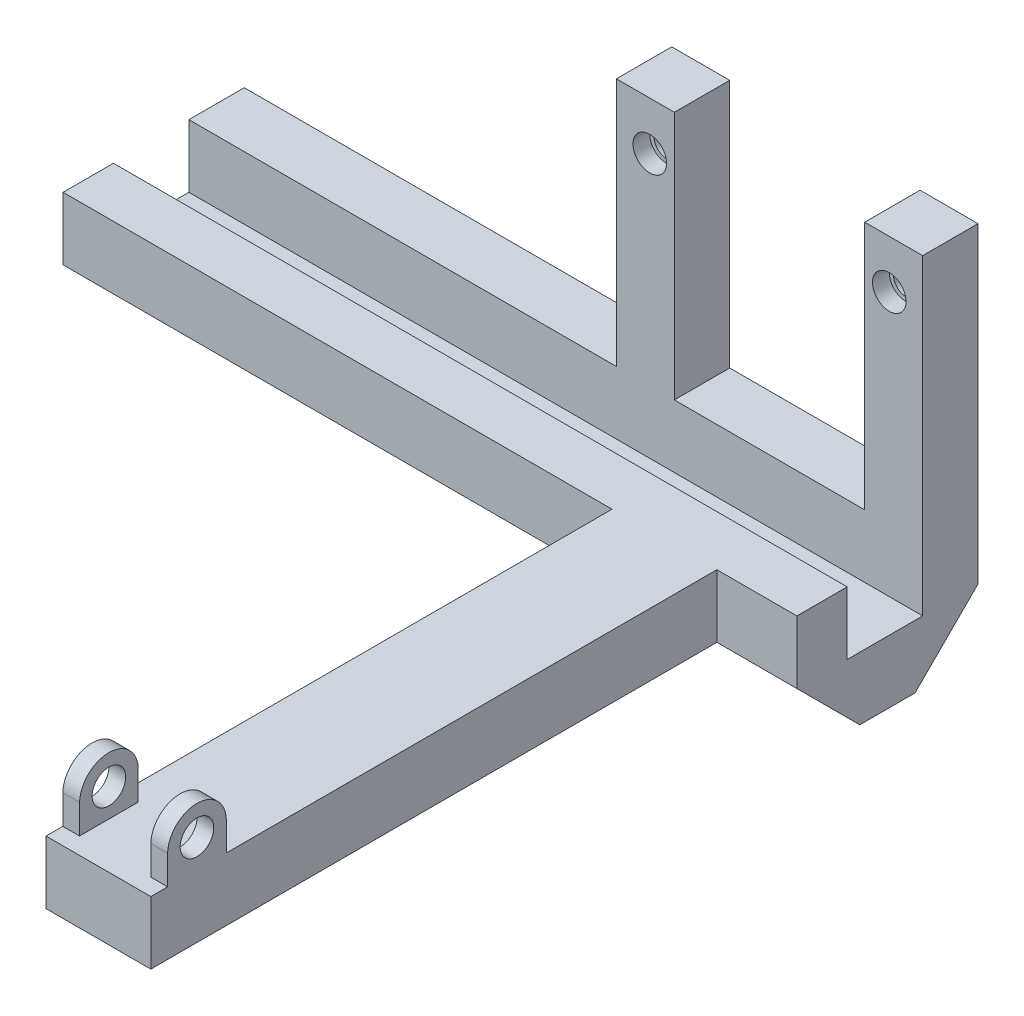
SolidWorks part; units mm, degrees
ref_plane "Front Plane" through (0, 0, 0) normal (0, 0, 1) x (1, 0, 0)
ref_plane "Top Plane" through (0, 0, 0) normal (0, 1, 0) x (1, 0, 0)
ref_plane "Right Plane" through (0, 0, 0) normal (1, 0, 0) x (0, 0, -1)
sketch "Sketch1" plane through (0, 0, 0) normal (0, 0, 1) x (1, 0, 0)
  line L0 (0, 0) -> (0, -26.56)
  line L17 (0, -26.56) -> (-71.9839, -26.56)
  line L18 (-71.9839, -26.56) -> (-71.9839, -11.56)
  line L19 (-71.9839, -11.56) -> (-52.61, -11.56)
  line L20 (-52.61, -11.56) -> (-52.61, 0)
  line L21 (-52.61, 0) -> (-37.61, 0)
  line L22 (-37.61, 0) -> (-37.61, -11.56)
  line L23 (-37.61, -11.56) -> (-15, -11.56)
  line L24 (-15, -11.56) -> (-15, 0)
  line L25 (-15, 0) -> (0, 0)
  dimension "D1" = 15
  dimension "D2" = 22.61
  dimension "D3" = 15
  dimension "D4" = 71.9839
  dimension "D5" = 15
  dimension "D6" = 0
  dimension "D7" = 11.56
extrude "Boss-Extrude1" add sketch "Sketch1" along normal blind 15
sketch "Sketch2" plane through (0, 0, 15) normal (0, 0, 1) x (1, 0, 0)
  line L0 (0, -26.56) -> (0, 0) construction
  line L1 (-71.9839, -26.56) -> (0, -26.56)
  line L2 (-71.9839, -26.56) -> (-71.9839, -19.06)
  line L3 (-71.9839, -19.06) -> (0, -19.06)
  line L4 (0, -26.56) -> (0, -19.06)
  dimension "D1" = 7.5
extrude "Boss-Extrude2" add sketch "Sketch2" along normal blind 15
sketch "Sketch3" plane through (0, -19.06, 0) normal (0, 1, 0) x (1, 0, 0)
  line L0 (0, -30) -> (0, -15) construction
  line L1 (-71.9839, -30) -> (0, -30)
  line L2 (-71.9839, -30) -> (-71.9839, -22.5)
  line L3 (-71.9839, -22.5) -> (0, -22.5)
  line L4 (0, -30) -> (0, -22.5)
extrude "Boss-Extrude3" add sketch "Sketch3" along normal blind 7.5
sketch "Sketch4" plane through (0, 0, 0) normal (1, 0, 0) x (0, 0, -1)
  line L0 (-30, -26.56) -> (0, -26.56) construction
  line L1 (-8.4, -26.56) -> (0, -26.56)
  line L2 (-8.4, -26.56) -> (-8.4, 0)
  line L3 (-8.4, 0) -> (0, 0)
  line L4 (0, -26.56) -> (0, 0)
  line L5 (-15, -19.06) -> (-15, 0) construction
  dimension "D1" = 6.6
extrude "Cut-Extrude1" cut sketch "Sketch4" against normal through all
sketch "Sketch5" plane through (0, 0, 8.4) normal (0, 0, -1) x (-1, 0, 0)
  line L0 (71.9839, -11.56) -> (71.9839, -26.56) construction
  line L1 (0, -26.56) -> (71.9839, -26.56)
  line L2 (0, -26.56) -> (0, -16.56)
  line L3 (0, -16.56) -> (71.9839, -16.56)
  line L4 (71.9839, -26.56) -> (71.9839, -16.56)
  dimension "D1" = 10
extrude "Boss-Extrude4" add sketch "Sketch5" along normal blind 23.8
sketch "Sketch6" plane through (-71.9839, 0, 0) normal (-1, 0, 0) x (0, 0, 1)
  line L1 (34.6627, -37.2189) -> (-26.9292, -37.2189)
  line L2 (34.6627, -37.2189) -> (34.6627, 2.9063)
  line L3 (34.6627, 2.9063) -> (-26.9292, 2.9063)
  line L4 (-26.9292, -37.2189) -> (-26.9292, 2.9063)
extrude "Cut-Extrude2" cut sketch "Sketch6" against normal blind 1.984
sketch "Esquisse1" plane through (0, 0, 15) normal (0, 0, 1) x (1, 0, 0)
  line L0 (-15, 0) -> (-15, -11.56) construction
  line L1 (-15, 0) -> (-4.91, 0)
  line L2 (-15, 0) -> (-15, -11.56)
  line L3 (-15, -11.56) -> (-4.91, -11.56)
  line L4 (-4.91, 0) -> (-4.91, -11.56)
  line L5 (0, 0) -> (-15, 0) construction
  line L6 (-15, -11.56) -> (-37.61, -11.56) construction
  line L7 (0, -19.06) -> (0, 0) construction
  dimension "D1" = 0
  dimension "D2" = 0
  dimension "D3" = 4.91
extrude "Enlèv. mat.-Extru.1" cut sketch "Esquisse1" against normal blind 10
sketch "Esquisse2" plane through (0, 0, 8.4) normal (0, 0, -1) x (-1, 0, 0)
  line L0 (4.91, -11.56) -> (37.61, -11.56) construction
  line L1 (27.61, -11.56) -> (32.52, -11.56)
  line L2 (27.61, -11.56) -> (27.61, 0)
  line L3 (27.61, 0) -> (32.52, 0)
  line L4 (32.52, -11.56) -> (32.52, 0)
  line L5 (4.91, -11.56) -> (4.91, 0) construction
  dimension "D1" = 22.7
  dimension "D2" = 4.91
  dimension "D3" = 11.56
extrude "Boss.-Extru.1" add sketch "Esquisse2" against normal blind 6.6
sketch "Esquisse3" plane through (0, 0, 30) normal (0, 0, 1) x (1, 0, 0)
  line L0 (-69.9999, -11.56) -> (0, -11.56) construction
  line L1 (-7.54, -11.56) -> (-20.04, -11.56)
  line L2 (-7.54, -11.56) -> (-7.54, -26.56)
  line L3 (-7.54, -26.56) -> (-20.04, -26.56)
  line L4 (-20.04, -11.56) -> (-20.04, -26.56)
  line L5 (-69.9999, -26.56) -> (0, -26.56) construction
  line L6 (0, -26.56) -> (0, -11.56) construction
  dimension "D1" = 12.5
  dimension "D2" = 7.54
extrude "Boss.-Extru.5" add sketch "Esquisse3" along normal blind 67.5
sketch "Esquisse4" plane through (0, -16.56, 0) normal (0, 1, 0) x (1, 0, 0)
  line L1 (-27.61, -8.4) -> (-4.91, -8.4)
  line L2 (-27.61, -8.4) -> (-27.61, 8.8)
  line L3 (-27.61, 8.8) -> (-4.91, 8.8)
  line L4 (-4.91, -8.4) -> (-4.91, 8.8)
  dimension "D1" = 17.2
  dimension "D2" = 22.7
extrude "Boss.-Extru.6" add sketch "Esquisse4" along normal blind 5
sketch "Esquisse5" plane through (0, 0, 8.4) normal (0, 0, -1) x (-1, 0, 0)
  line L1 (37.61, 0) -> (52.61, 0)
  line L2 (37.61, 0) -> (37.61, -11.56)
  line L3 (37.61, -11.56) -> (52.61, -11.56)
  line L4 (52.61, 0) -> (52.61, -11.56)
extrude "Enlèv. mat.-Extru.4" cut sketch "Esquisse5" against normal through all
sketch "Sketch7" plane through (0, 0, 0) normal (1, 0, 0) x (0, 0, -1)
  line L1 (-22.5, -11.56) -> (-24, -11.56)
  line L2 (-22.5, -11.56) -> (-22.5, -19.06)
  line L3 (-22.5, -19.06) -> (-24, -19.06)
  line L4 (-24, -11.56) -> (-24, -19.06)
  dimension "D1" = 1.5
  dimension "D2" = 7.5
extrude "Cut-Extrude3" cut sketch "Sketch7" against normal through all
sketch "Sketch8" plane through (0, 0, 97.5) normal (0, 0, 1) x (1, 0, 0)
  line L0 (-69.9999, -26.56) -> (-20.04, -26.56) construction
  line L1 (-20.04, -11.56) -> (-22.04, -11.56)
  line L2 (-20.04, -11.56) -> (-20.04, -26.56)
  line L3 (-20.04, -26.56) -> (-22.04, -26.56)
  line L4 (-22.04, -11.56) -> (-22.04, -26.56)
  dimension "D1" = 2
extrude "Boss-Extrude5" add sketch "Sketch8" against normal up to next
sketch "Sketch9" plane through (0, 0, 97.5) normal (0, 0, 1) x (1, 0, 0)
  line L0 (-22.04, -26.56) -> (-7.54, -26.56) construction
  line L1 (-7.54, -11.56) -> (-9.54, -11.56)
  line L2 (-7.54, -11.56) -> (-7.54, -26.56)
  line L3 (-7.54, -26.56) -> (-9.54, -26.56)
  line L4 (-9.54, -11.56) -> (-9.54, -26.56)
  dimension "D1" = 2
extrude "Cut-Extrude4" cut sketch "Sketch9" against normal blind 67.5
sketch "Sketch10" plane through (0, 0, 15) normal (0, 0, 1) x (1, 0, 0)
  line L0 (-9.54, -11.56) -> (0, -11.56) construction
  line L1 (-4.91, 0) -> (-6.91, 0)
  line L2 (-4.91, 0) -> (-4.91, -11.56)
  line L3 (-4.91, -11.56) -> (-6.91, -11.56)
  line L4 (-6.91, 0) -> (-6.91, -11.56)
  dimension "D1" = 2
extrude "Boss-Extrude6" add sketch "Sketch10" against normal up to vertex
sketch "Sketch12" plane through (0, 0, 15) normal (0, 0, 1) x (1, 0, 0)
  line L1 (-27.61, 0) -> (-29.61, 0)
  line L2 (-27.61, 0) -> (-27.61, -11.56)
  line L3 (-27.61, -11.56) -> (-29.61, -11.56)
  line L4 (-29.61, 0) -> (-29.61, -11.56)
  dimension "D1" = 2
  dimension "D2" = 11.56
extrude "Cut-Extrude6" cut sketch "Sketch12" against normal through all
sketch "Sketch13" plane through (0, 0, 15) normal (0, 0, 1) x (1, 0, 0)
  line L0 (-32.52, -11.56) -> (-69.9999, -11.56) construction
  line L1 (-32.52, 0) -> (-36.52, 0)
  line L2 (-32.52, 0) -> (-32.52, -11.56)
  line L3 (-32.52, -11.56) -> (-36.52, -11.56)
  line L4 (-36.52, 0) -> (-36.52, -11.56)
  dimension "D1" = 4
extrude "Boss-Extrude7" add sketch "Sketch13" against normal up to vertex (6.6 mm away) up to point (-32.52, 0, 8.4)
sketch "Sketch14" plane through (0, -11.56, 0) normal (0, 1, 0) x (1, 0, 0)
  line L0 (-4.91, 8.8) -> (-27.61, 8.8) construction
  line L1 (-4.91, -8.4) -> (-6.91, -8.4)
  line L2 (-4.91, -8.4) -> (-4.91, 8.8)
  line L3 (-4.91, 8.8) -> (-6.91, 8.8)
  line L4 (-6.91, -8.4) -> (-6.91, 8.8)
  dimension "D1" = 2
extrude "Cut-Extrude7" cut sketch "Sketch14" against normal up to vertex (5 mm away) up to point (-4.91, -16.56, -8.8)
sketch "Sketch15" plane through (0, -11.56, 0) normal (0, 1, 0) x (1, 0, 0)
  line L1 (-27.61, -8.4) -> (-29.61, -8.4)
  line L2 (-27.61, -8.4) -> (-27.61, 8.8)
  line L3 (-27.61, 8.8) -> (-29.61, 8.8)
  line L4 (-29.61, -8.4) -> (-29.61, 8.8)
  line L5 (-6.91, 8.8) -> (-27.61, 8.8) construction
  dimension "D1" = 2
  dimension "D2" = 0
extrude "Boss-Extrude8" add sketch "Sketch15" against normal up to vertex (15 mm away)
sketch "Sketch16" plane through (0, -16.56, 0) normal (0, 1, 0) x (1, 0, 0)
  line L0 (-69.9999, 15.4) -> (0, 15.4) construction
  line L1 (-69.9999, -8.4) -> (-29.61, -8.4)
  line L2 (-69.9999, -8.4) -> (-69.9999, 15.4)
  line L3 (-69.9999, 15.4) -> (-29.61, 15.4)
  line L4 (-29.61, -8.4) -> (-29.61, 15.4)
  dimension "D1" = 40.3899
extrude "Cut-Extrude8" cut sketch "Sketch16" against normal through all
sketch "Sketch21" plane through (0, -16.56, 0) normal (0, 1, 0) x (1, 0, 0)
  line L0 (-29.61, 15.4) -> (0, 15.4) construction
  line L1 (0, -8.4) -> (-6.91, -8.4)
  line L2 (0, -8.4) -> (0, 15.4)
  line L3 (0, 15.4) -> (-6.91, 15.4)
  line L4 (-6.91, -8.4) -> (-6.91, 15.4)
extrude "Cut-Extrude11" cut sketch "Sketch21" against normal through all
sketch "Sketch22" plane through (0, -16.56, 0) normal (0, 1, 0) x (1, 0, 0)
  line L1 (-29.61, 15.4) -> (-6.91, 15.4)
  line L2 (-29.61, 15.4) -> (-29.61, 8.8)
  line L3 (-29.61, 8.8) -> (-6.91, 8.8)
  line L4 (-6.91, 15.4) -> (-6.91, 8.8)
extrude "Cut-Extrude12" cut sketch "Sketch22" against normal through all
sketch "Sketch23" plane through (-29.61, 0, 0) normal (-1, 0, 0) x (0, 0, 1)
  line L0 (8.4, -26.56) -> (8.4, -11.56) construction
  line L1 (-8.8, -26.56) -> (8.4, -26.56)
  line L2 (-8.8, -26.56) -> (-8.8, -19.06)
  line L3 (-8.8, -19.06) -> (8.4, -19.06)
  line L4 (8.4, -26.56) -> (8.4, -19.06)
extrude "Cut-Extrude13" cut sketch "Sketch23" against normal through all
sketch "Sketch26" plane through (0, 0, 8.4) normal (0, 0, -1) x (-1, 0, 0)
  line L0 (6.91, 0) -> (0, 0) construction
  line L1 (0, 0) -> (0, -26.56) construction
  circle A0 centre (3.98, -5.74) radius 1.05
  dimension "D1" = 5.74
  dimension "D2" = 3.98
  dimension "D3" = 2.1
extrude "Cut-Extrude15" cut sketch "Sketch26" against normal through all
sketch "Sketch27" plane through (0, 0, 8.4) normal (0, 0, -1) x (-1, 0, 0)
  line L1 (36.52, 0) -> (36.52, -11.56) construction
  line L2 (36.52, 0) -> (29.61, 0) construction
  circle A0 centre (32.54, -5.74) radius 1.05
  dimension "D1" = 2.1
  dimension "D2" = 3.98
  dimension "D3" = 5.74
extrude "Cut-Extrude16" cut sketch "Sketch27" against normal through all
sketch "Sketch28" plane through (-22.04, 0, 0) normal (-1, 0, 0) x (0, 0, 1)
  line L0 (97.5, -11.56) -> (97.5, -26.56) construction
  line L1 (30, -26.56) -> (97.5, -26.56)
  line L2 (30, -26.56) -> (30, -19.06)
  line L3 (30, -19.06) -> (97.5, -19.06)
  line L4 (97.5, -26.56) -> (97.5, -19.06)
extrude "Cut-Extrude17" cut sketch "Sketch28" against normal through all
sketch "Sketch29" plane through (-69.9999, 0, 0) normal (-1, 0, 0) x (0, 0, 1)
  line L0 (8.4, -19.06) -> (15.9, -26.56)
  line L1 (8.4, -11.56) -> (8.4, -26.56) construction
  line L2 (8.4, -26.56) -> (30, -26.56) construction
  line L3 (15.9, -26.56) -> (8.4, -26.56)
  line L4 (8.4, -26.56) -> (8.4, -19.06)
extrude "Cut-Extrude18" cut sketch "Sketch29" against normal through all
sketch "Sketch30" plane through (-69.9999, 0, 0) normal (-1, 0, 0) x (0, 0, 1)
  line L0 (30, -19.06) -> (22.5, -26.56)
  line L1 (15.9, -26.56) -> (30, -26.56) construction
  line L2 (22.5, -26.56) -> (30, -26.56)
  line L3 (30, -26.56) -> (30, -11.56) construction
  line L4 (30, -26.56) -> (30, -19.06)
  dimension "D1" = 45
extrude "Cut-Extrude19" cut sketch "Sketch30" against normal through all
sketch "Sketch32" plane through (0, -11.56, 0) normal (0, 1, 0) x (1, 0, 0)
  line L0 (-22.04, -30) -> (-22.04, -97.5) construction
  line L1 (-22.04, -95.5) -> (-20.04, -95.5)
  line L2 (-22.04, -95.5) -> (-22.04, -88.5)
  line L3 (-22.04, -88.5) -> (-20.04, -88.5)
  line L4 (-20.04, -95.5) -> (-20.04, -88.5)
  line L5 (-9.54, -97.5) -> (-22.04, -97.5) construction
  dimension "D1" = 2
  dimension "D2" = 7
  dimension "D3" = 2
extrude "Boss-Extrude10" add sketch "Sketch32" along normal blind 10
sketch "Sketch33" plane through (0, -11.56, 0) normal (0, 1, 0) x (1, 0, 0)
  line L0 (-9.54, -30) -> (-9.54, -97.5) construction
  line L1 (-9.54, -95.5) -> (-11.54, -95.5)
  line L2 (-9.54, -95.5) -> (-9.54, -88.5)
  line L3 (-9.54, -88.5) -> (-11.54, -88.5)
  line L4 (-11.54, -95.5) -> (-11.54, -88.5)
  line L5 (-9.54, -97.5) -> (-22.04, -97.5) construction
  dimension "D1" = 7
  dimension "D2" = 2
  dimension "D3" = 2
extrude "Boss-Extrude11" add sketch "Sketch33" along normal blind 10
sketch "Sketch37" plane through (-9.54, 0, 0) normal (1, 0, 0) x (0, 0, -1)
  line L0 (-95.5, -5.06) -> (-95.5, -1.56)
  line L1 (-95.5, -1.56) -> (-88.5, -1.56) construction
  line L2 (-88.5, -1.56) -> (-88.5, -11.56) construction
  line L3 (-88.5, -5.06) -> (-95.5, -5.06)
  line L4 (-95.5, -1.56) -> (-95.5, -11.56) construction
  line L5 (-95.5, -1.56) -> (-92, -1.56)
  line L6 (-88.5, -1.56) -> (-88.5, -5.06)
  line L7 (-88.5, -5.06) -> (-88.5, -1.56)
  arc A0 (-92, -1.56) -> (-88.5, -5.06) centre (-92, -5.06) cw
  arc A1 (-95.5, -5.06) -> (-92, -1.56) centre (-92, -5.06) cw
  line M8 (-88.5, -11.56) -> (-88.5, -1.56)
  line M9 (-88.5, -1.56) -> (-95.5, -1.56)
  line M10 (-95.5, -1.56) -> (-95.5, -11.56)
extrude "Cut-Extrude20" cut sketch "Sketch37" against normal through all contours A1 M10 M9 | A0 M9 M8
sketch "Sketch39" plane through (-9.54, 0, 0) normal (1, 0, 0) x (0, 0, -1)
  line L1 (-95.5, -5.06) -> (-95.5, -11.56) construction
  line L2 (-88.5, -5.06) -> (-88.5, -11.56) construction
  line L3 (-88.5, -8.31) -> (-88.5, -5.06)
  line L4 (-95.5, -5.06) -> (-95.5, -8.31)
  arc A0 (-95.5, -8.31) -> (-88.5, -8.31) centre (-92, -8.1939) cw
  arc A1 (-88.5, -5.06) -> (-95.5, -5.06) centre (-92, -5.06) ccw
  arc M2 (-88.5, -5.06) -> (-95.5, -5.06) centre (-92, -5.06) ccw
  line M3 (-95.5, -5.06) -> (-95.5, -11.56)
extrude "Cut-Extrude21" cut sketch "Sketch39" against normal through all contours A0 L3 M3 M2
sketch "Sketch40" plane through (-9.54, 0, 0) normal (1, 0, 0) x (0, 0, -1)
  circle A0 centre (-92, -8.1939) radius 2
  arc A1 (-88.5, -8.0779) -> (-95.5, -8.0779) centre (-92, -8.1939) ccw construction
  dimension "D1" = 0
  dimension "D2" = 4
extrude "Cut-Extrude22" cut sketch "Sketch40" against normal through all
sketch "Sketch41" plane through (-69.9999, 0, 0) normal (-1, 0, 0) x (0, 0, 1)
  line L0 (8.4, -11.56) -> (8.4, -19.06)
  line L1 (8.4, -19.06) -> (15.9, -26.56)
  line L2 (15.9, -26.56) -> (22.5, -26.56)
  line L3 (22.5, -26.56) -> (30, -19.06)
  line L4 (30, -19.06) -> (30, -11.56)
  line L5 (30, -11.56) -> (24, -11.56)
  line L6 (24, -11.56) -> (24, -19.06)
  line L7 (24, -19.06) -> (15, -19.06)
  line L8 (15, -19.06) -> (15, -11.56)
  line L9 (15, -11.56) -> (8.4, -11.56)
extrude "Boss-Extrude12" add sketch "Sketch41" along normal blind 17.5
sketch "Sketch42" plane through (0, 0, 0) normal (0, 1, 0) x (1, 0, 0)
  line L1 (-6.91, -8.4) -> (0, -8.4)
  line L2 (-6.91, -8.4) -> (-6.91, -15)
  line L3 (-6.91, -15) -> (0, -15)
  line L4 (0, -8.4) -> (0, -15)
  line L5 (-29.61, -8.4) -> (-36.52, -8.4)
  line L6 (-29.61, -8.4) -> (-29.61, -15)
  line L7 (-29.61, -15) -> (-36.52, -15)
  line L8 (-36.52, -8.4) -> (-36.52, -15)
extrude "Boss-Extrude13" add sketch "Sketch42" along normal blind 18.1497
sketch "Sketch43" plane through (0, 0, 15) normal (0, 0, 1) x (1, 0, 0)
  line L2 (-6.91, 18.1497) -> (-6.91, -11.56) construction
  circle A0 centre (-32.54, 12.4097) radius 1.5
  circle A1 centre (-32.54, -5.74) radius 1.05 construction
  circle A2 centre (-3.98, 12.4097) radius 1.5
  circle A3 centre (-3.98, -5.74) radius 1.05 construction
  dimension "D1" = 18.1497
  dimension "D2" = 18.1497
  dimension "D4" = 3
  dimension "D5" = 3
  dimension "D3" = 0
  dimension "D6" = 2.93
extrude "Cut-Extrude23" cut sketch "Sketch43" against normal through all
sketch "Sketch44" plane through (0, 0, 15) normal (0, 0, 1) x (1, 0, 0)
  circle A0 centre (-32.54, 12.4097) radius 2
  circle A1 centre (-3.98, 12.4097) radius 2
  dimension "D1" = 4
  dimension "D2" = 4
extrude "Cut-Extrude24" cut sketch "Sketch44" against normal blind 2
sketch "Sketch45" plane through (0, 0, 15) normal (0, 0, 1) x (1, 0, 0)
  line L1 (-34.0153, -3.7879) -> (-30.7704, -3.7879)
  line L2 (-34.0153, -3.7879) -> (-34.0153, -7.2182)
  line L3 (-34.0153, -7.2182) -> (-30.7704, -7.2182)
  line L4 (-30.7704, -3.7879) -> (-30.7704, -7.2182)
  line L5 (-1.8446, -3.7879) -> (-6.0166, -3.7879)
  line L6 (-1.8446, -3.7879) -> (-1.8446, -7.2182)
  line L7 (-1.8446, -7.2182) -> (-6.0166, -7.2182)
  line L8 (-6.0166, -3.7879) -> (-6.0166, -7.2182)
extrude "Boss-Extrude14" add sketch "Sketch45" against normal blind 6.6
sketch "Sketch46" plane through (0, -11.56, 0) normal (0, 1, 0) x (1, 0, 0)
  line L1 (-29.61, -8.4) -> (-6.91, -8.4)
  line L2 (-29.61, -8.4) -> (-29.61, 8.8)
  line L3 (-29.61, 8.8) -> (-6.91, 8.8)
  line L4 (-6.91, -8.4) -> (-6.91, 8.8)
extrude "Cut-Extrude25" cut sketch "Sketch46" against normal through all
